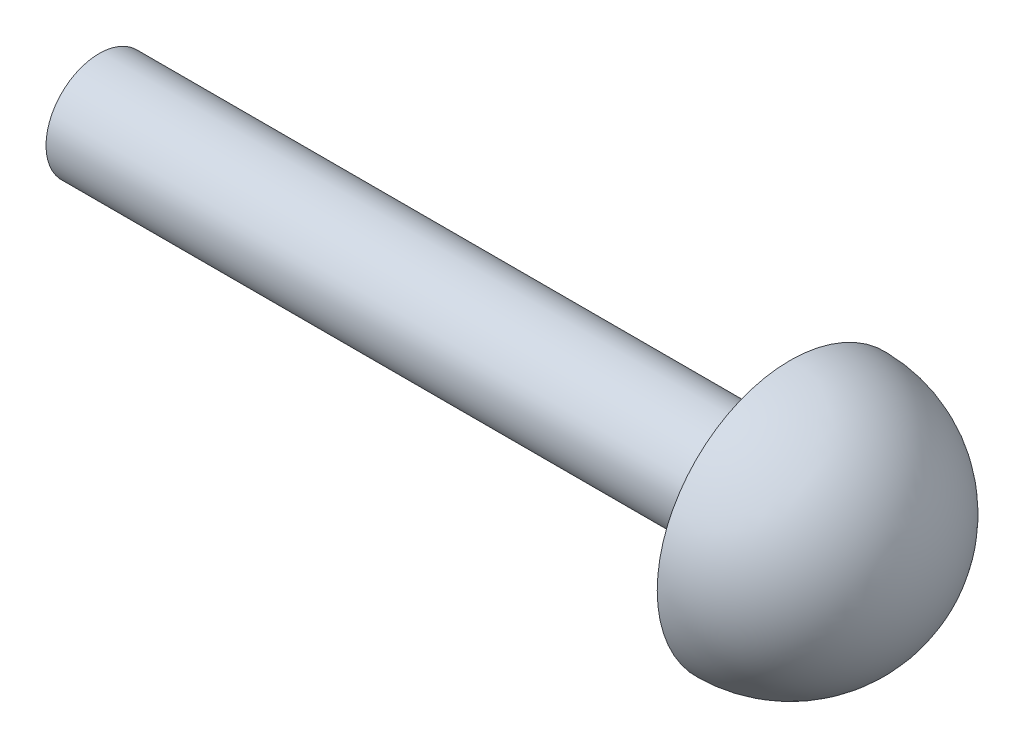
SolidWorks part; units mm, degrees
ref_plane "Front Plane" through (0, 0, 0) normal (0, 0, 1) x (1, 0, 0)
ref_plane "Top Plane" through (0, 0, 0) normal (0, 1, 0) x (1, 0, 0)
ref_plane "Right Plane" through (0, 0, 0) normal (1, 0, 0) x (0, 0, -1)
sketch "Sketch1" plane through (0, 0, 0) normal (0, 0, 1) x (1, 0, 0)
  line L0 (0, 0) -> (0, 2)
  line L1 (0, 2) -> (26, 2)
  line L2 (26, 2) -> (26, 5)
  line L3 (0, 0) -> (31, 0)
  arc A0 (31, 0) -> (26, 5) centre (26, 0) ccw
  point P7 (26, 4.2372)
  point P8 (26, 0)
  dimension "D1" = 5
  dimension "D2" = 26
  dimension "D3" = 2
revolve "Revolve1" add sketch "Sketch1" angle 360 about L3
